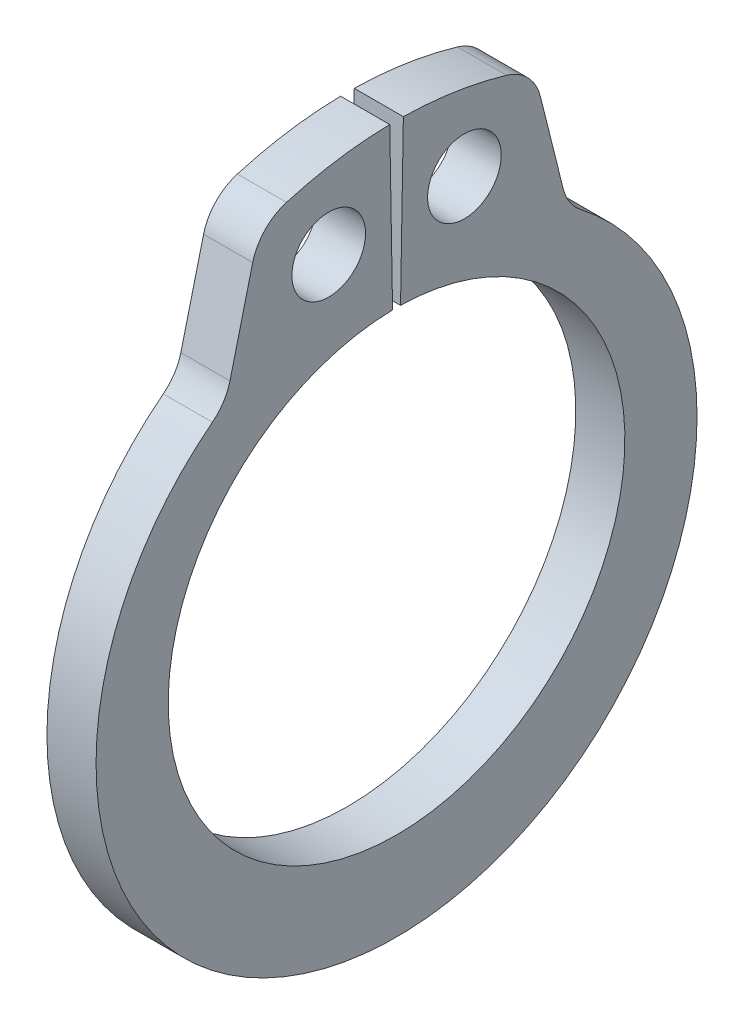
SolidWorks part; units mm, degrees
ref_plane "Front" through (0, 0, 0) normal (0, 0, 1) x (1, 0, 0)
ref_plane "Top" through (0, 0, 0) normal (0, 1, 0) x (1, 0, 0)
ref_plane "Right" through (0, 0, 0) normal (1, 0, 0) x (0, 0, -1)
sketch "Sketch1" plane through (0, 0, 0) normal (1, 0, 0) x (0, 0, -1)
  line L0 (0, 0) -> (0, 4.65) construction
  line L1 (-0.0812, 4.6493) -> (-0.1387, 7.9488)
  line L2 (-0.1387, 7.9488) -> (-2.6816, 7.9044) construction
  line L3 (-2.6816, 7.9044) -> (-3.4799, 4.7024) construction
  line L4 (0.1387, 7.9488) -> (0.0812, 4.6493)
  line L5 (0.1387, 7.9488) -> (2.6816, 7.9044) construction
  line L6 (2.6816, 7.9044) -> (3.4799, 4.7024) construction
  line L7 (-3.4799, 4.7024) -> (-2.7661, 3.7378) construction
  line L8 (3.4799, 4.7024) -> (2.7661, 3.7378) construction
  line L9 (0, -4.65) -> (0, -6.45) construction
  line L10 (-2.6816, 7.9044) -> (-0.0812, 4.6493) construction
  line L12 (0, 4.65) -> (0, 7.95) construction
  line L13 (2.7969, 7.4418) -> (3.4799, 4.7024)
  line L14 (-2.7969, 7.4418) -> (-3.4799, 4.7024)
  circle A0 centre (0, 0) radius 4.65 construction
  arc A1 (-0.0812, 4.6493) -> (0.0812, 4.6493) centre (0, 0) ccw
  circle A2 centre (0, -0.3309) radius 6.1191 construction
  circle A4 centre (-1.3814, 6.2768) radius 0.75
  circle A5 centre (1.3814, 6.2768) radius 0.75
  arc A6 (-3.4799, 4.7024) -> (3.4799, 4.7024) centre (0, -0.3309) ccw
  arc A7 (0.1387, 7.9488) -> (2.7969, 7.4418) centre (0, 0) cw
  arc A8 (-0.1387, 7.9488) -> (-2.7969, 7.4418) centre (0, 0) ccw
  dimension "A" = 9.3
  dimension "Hole" = 1.5
  dimension "Smin" = 1.2
  dimension "D1" = 75
  dimension "Angle" = 1
  dimension "H" = 3.3
extrude "Extrude1" add sketch "Sketch1" along normal mid plane 1
fillet "Fillet1" radius 1 4 edges at (0, 4.7024, 3.4799) (0, 7.4418, 2.7969) (0, 7.4418, -2.7969) (0, 4.7024, -3.4799)
sketch "Sketch2" plane through (0, 0, 0) normal (0, 0, 1) x (1, 0, 0)
  line L0 (-2.75, 0) -> (8.25, 0)
  line L1 (8.25, 0) -> (8.25, -5)
  line L2 (-2.75, 0) -> (-2.75, -4.8)
  line L3 (8.25, -5) -> (0.55, -5)
  line L4 (0.55, -5) -> (0.55, -4.8)
  line L5 (0.55, -4.8) -> (-0.55, -4.8)
  line L6 (-0.55, -4.8) -> (-0.55, -5)
  line L7 (-0.55, -5) -> (-2.75, -5) construction
  line L8 (-2.75, -5) -> (-2.75, 0) construction
  line L9 (0, -4.8) -> (0, 0) construction
  line L10 (8.25, 0) -> (14.0551, 0) construction
  line L11 (-2.75, -4.8) -> (-2.55, -5)
  line L12 (-2.55, -5) -> (-0.55, -5)
  dimension "D2" = 11
  dimension "D3" = 2.75
  dimension "D1" = 45
revolve "Revolve1" [suppressed] add sketch "Sketch2" angle 360 about L10
equation "\"D2@Sketch2\" = \"W@Sketch2\"*10"
equation "\"D3@Sketch2\" = \"D2@Sketch2\"/4"
equation "\"Smin@Sketch1\" = \"Smax@Sketch1\"/1.5"
equation "\"D1@Fillet1\" = \"D1@Extrude1\""
